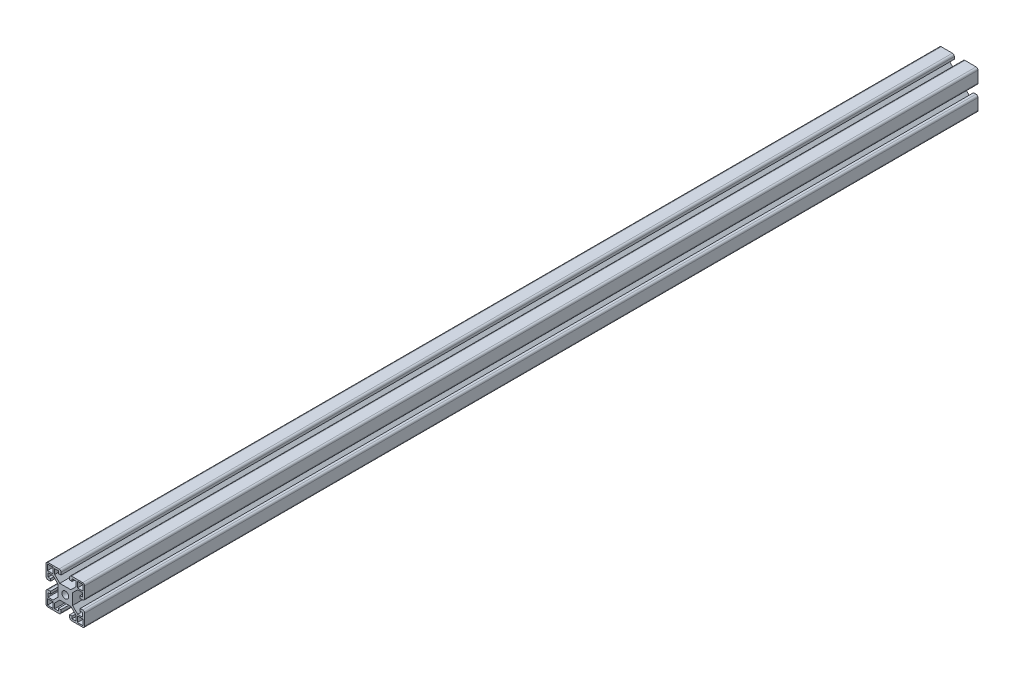
SolidWorks part; units mm, degrees
ref_plane "Alzado" through (0, 0, 0) normal (0, 0, 1) x (1, 0, 0)
ref_plane "Planta" through (0, 0, 0) normal (0, 1, 0) x (1, 0, 0)
ref_plane "Vista lateral" through (0, 0, 0) normal (1, 0, 0) x (0, 0, -1)
sketch "Croquis1" plane through (0, 0, 0) normal (0, 0, 1) x (1, 0, 0)
  line L1 (-20, -20) -> (20, -20)
  line L2 (-20, -20) -> (-20, 20)
  line L3 (-20, 20) -> (20, 20)
  line L4 (20, -20) -> (20, 20)
  line L5 (-20, -20) -> (20, 20) construction
  line L6 (-20, 20) -> (20, -20) construction
  point P0 (0, 0)
  dimension "D1" = 40
  dimension "D2" = 40
extrude "Saliente-Extruir1" add sketch "Croquis1" along normal blind 924.8
sketch "Croquis2" plane through (0, 0, 924.8) normal (0, 0, 1) x (1, 0, 0)
  line L0 (-7.5, 7.5) -> (-20, 20) construction
  line L1 (5.7336, -7.5014) -> (-5.7336, -7.5014)
  line L2 (7.5013, -5.7336) -> (7.5013, 5.7336)
  line L3 (5.7336, 7.5014) -> (-5.7336, 7.5014)
  line L4 (-7.5013, -5.7336) -> (-7.5013, 5.7336)
  line L5 (7.5, -7.5) -> (-7.5, 7.5) construction
  line L6 (7.5, 7.5) -> (-7.5, -7.5) construction
  line L7 (-5.7336, 7.5014) -> (-11, 12.7678)
  line L8 (-7.5013, 5.7336) -> (-12.7678, 11)
  line L9 (-20, 20) -> (-20, -20) construction
  line L10 (-18.5, 12.5) -> (-12.5, 12.5)
  line L11 (-18.5, 12.5) -> (-18.5, 18.5)
  line L12 (-18.5, 18.5) -> (-12.5, 18.5)
  line L13 (-12.5, 12.5) -> (-12.5, 18.5)
  line L14 (-18.5, 12.5) -> (-12.5, 18.5) construction
  line L15 (-18.5, 18.5) -> (-12.5, 12.5) construction
  line L16 (-11, 12.7678) -> (-11, 18)
  line L17 (-11, 18) -> (-7, 18)
  line L18 (-7, 18) -> (-7, 15.5)
  line L19 (-7, 15.5) -> (-4.5, 15.5)
  line L20 (-4.5, 15.5) -> (-4.5, 20)
  line L21 (20, 20) -> (-20, 20) construction
  line L22 (0, 20) -> (0, -20) construction
  line L23 (-20, -20) -> (20, -20) construction
  line L24 (-12.7678, 11) -> (-17.8676, 11)
  line L25 (-17.8676, 11) -> (-17.8676, 7)
  line L26 (-17.8676, 7) -> (-15.3676, 7)
  line L27 (-15.3676, 7) -> (-15.3676, 4.5)
  line L28 (-15.3676, 4.5) -> (-20, 4.5)
  line L29 (18.5, 18.5) -> (12.5, 12.5) construction
  line L30 (18.5, 12.5) -> (12.5, 18.5) construction
  line L31 (7.5, 7.5) -> (20, 20) construction
  line L32 (15.3676, 4.5) -> (20, 4.5)
  line L33 (15.3676, 7) -> (15.3676, 4.5)
  line L34 (17.8676, 7) -> (15.3676, 7)
  line L35 (17.8676, 11) -> (17.8676, 7)
  line L36 (12.7678, 11) -> (17.8676, 11)
  line L37 (4.5, 15.5) -> (4.5, 20)
  line L38 (7, 15.5) -> (4.5, 15.5)
  line L39 (7, 18) -> (7, 15.5)
  line L40 (11, 18) -> (7, 18)
  line L41 (11, 12.7678) -> (11, 18)
  line L42 (12.5, 12.5) -> (12.5, 18.5)
  line L43 (18.5, 18.5) -> (12.5, 18.5)
  line L44 (18.5, 12.5) -> (18.5, 18.5)
  line L45 (18.5, 12.5) -> (12.5, 12.5)
  line L46 (7.5013, 5.7336) -> (12.7678, 11)
  line L47 (5.7336, 7.5014) -> (11, 12.7678)
  line L48 (20, 0) -> (-20, 0) construction
  line L49 (20, -20) -> (20, 20) construction
  line L50 (7.5, -7.5) -> (20, -20) construction
  line L51 (18.5, -12.5) -> (12.5, -18.5) construction
  line L52 (18.5, -18.5) -> (12.5, -12.5) construction
  line L53 (-18.5, -18.5) -> (-12.5, -12.5) construction
  line L54 (-18.5, -12.5) -> (-12.5, -18.5) construction
  line L55 (-7.5, -7.5) -> (-20, -20) construction
  line L56 (5.7336, -7.5014) -> (11, -12.7678)
  line L57 (7.5013, -5.7336) -> (12.7678, -11)
  line L58 (18.5, -12.5) -> (12.5, -12.5)
  line L59 (18.5, -12.5) -> (18.5, -18.5)
  line L60 (18.5, -18.5) -> (12.5, -18.5)
  line L61 (12.5, -12.5) -> (12.5, -18.5)
  line L62 (11, -12.7678) -> (11, -18)
  line L63 (11, -18) -> (7, -18)
  line L64 (7, -18) -> (7, -15.5)
  line L65 (7, -15.5) -> (4.5, -15.5)
  line L66 (4.5, -15.5) -> (4.5, -20)
  line L67 (12.7678, -11) -> (17.8676, -11)
  line L68 (17.8676, -11) -> (17.8676, -7)
  line L69 (17.8676, -7) -> (15.3676, -7)
  line L70 (15.3676, -7) -> (15.3676, -4.5)
  line L71 (15.3676, -4.5) -> (20, -4.5)
  line L72 (-15.3676, -4.5) -> (-20, -4.5)
  line L73 (-15.3676, -7) -> (-15.3676, -4.5)
  line L74 (-17.8676, -7) -> (-15.3676, -7)
  line L75 (-17.8676, -11) -> (-17.8676, -7)
  line L76 (-12.7678, -11) -> (-17.8676, -11)
  line L77 (-4.5, -15.5) -> (-4.5, -20)
  line L78 (-7, -15.5) -> (-4.5, -15.5)
  line L79 (-7, -18) -> (-7, -15.5)
  line L80 (-11, -18) -> (-7, -18)
  line L81 (-11, -12.7678) -> (-11, -18)
  line L82 (-12.5, -12.5) -> (-12.5, -18.5)
  line L83 (-18.5, -18.5) -> (-12.5, -18.5)
  line L84 (-18.5, -12.5) -> (-18.5, -18.5)
  line L85 (-18.5, -12.5) -> (-12.5, -12.5)
  line L86 (-7.5013, -5.7336) -> (-12.7678, -11)
  line L87 (-5.7336, -7.5014) -> (-11, -12.7678)
  line L88 (5.7336, -7.5014) -> (-5.7336, -7.5014)
  line L89 (-20, -4.5) -> (-20, 4.5)
  line L90 (20, 4.5) -> (20, -4.5)
  line L91 (-4.5, -20) -> (4.5, -20)
  line L92 (-4.5, 20) -> (4.5, 20)
  circle A0 centre (0, 0) radius 3.5
  point P0 (0, 0)
  point P14 (-15.5, 15.5)
  point P56 (15.5, 15.5)
  point P99 (15.5, -15.5)
  point P100 (-15.5, -15.5)
  line M20 (20, -20) -> (20, 20)
  line M21 (20, 20) -> (-20, 20)
  line M22 (-20, 20) -> (-20, -20)
  line M23 (-20, -20) -> (20, -20)
  dimension "D3" = 7
  dimension "D1" = 15
  dimension "D2" = 15
  dimension "D4" = 1.25
  dimension "D5" = 1.25
  dimension "D6" = 1.5
  dimension "D7" = 6
  dimension "D8" = 6
  dimension "D9" = 1.5
  dimension "D10" = 2
  dimension "D11" = 4
  dimension "D12" = 2.5
  dimension "D13" = 2.5
  dimension "D14" = 1.5
  dimension "D15" = 4
  dimension "D16" = 2.5
  dimension "D17" = 2.5
extrude "Cortar-Extruir2" cut sketch "Croquis2" against normal up to surface (924.8 mm away) contours L10 L13 L12 L11 | L3 L47 L41 L40 L39 L38 L37 L20 L19 L18 L17 L16 L7 M21 | L45 L44 L43 L42 | L70 L71 L32 L33 L34 L35 L36 L46 L2 L57 L67 L68 L69 M20 | L86 L4 L8 L24 L25 L26 L27 L28 L72 L73 L74 L75 L76 M22 | A0 | L1 L87 L81 L80 L79 L78 L77 L66 L65 L64 L63 L62 L56 M23 | L85 L84 L83 L82 | L58 L61 L60 L59 up to face at (0, 0, 0)
fillet "Redondeo1" radius 2 4 edges at (-20, -20, 462.4) (-20, 20, 462.4) (20, -20, 462.4) (20, 20, 462.4)
fillet "Redondeo2" radius 2 8 edges at (-20, -4.5, 462.4) (-20, 4.5, 462.4) (-4.5, -20, 462.4) (4.5, -20, 462.4) (20, 4.5, 462.4) (20, -4.5, 462.4) (4.5, 20, 462.4) (-4.5, 20, 462.4)
